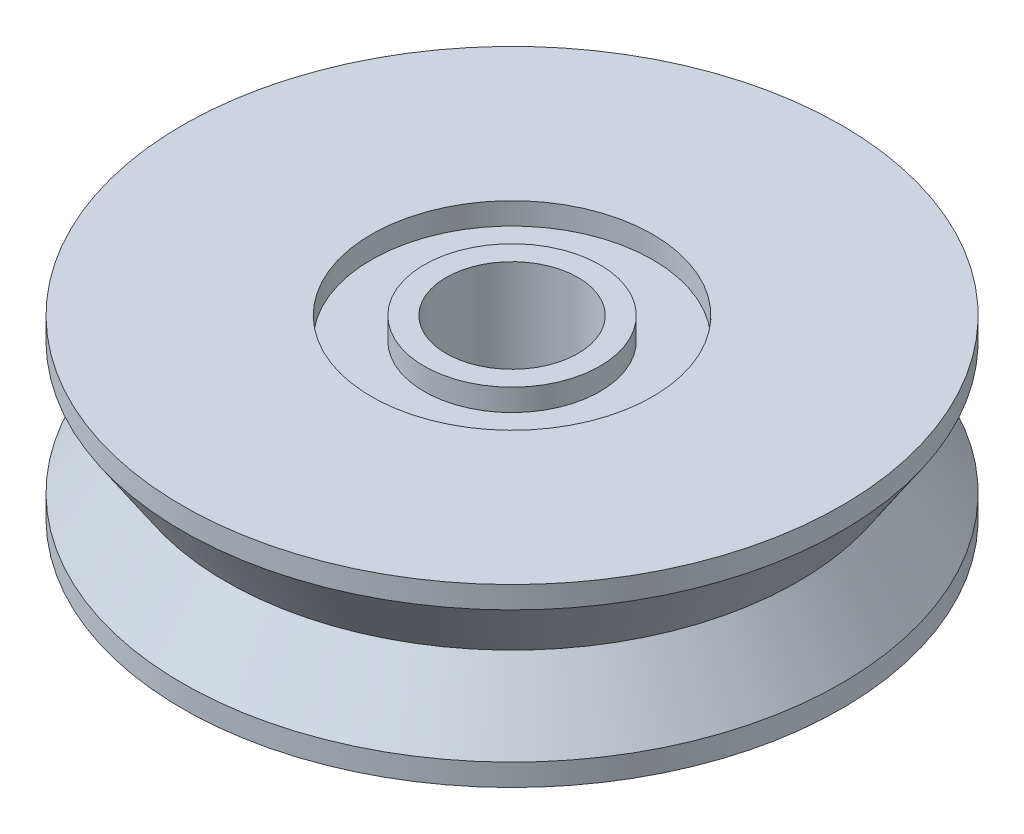
SolidWorks part; units mm, degrees
ref_plane "Front Plane" through (0, 0, 0) normal (0, 0, 1) x (1, 0, 0)
ref_plane "Top Plane" through (0, 0, 0) normal (0, 1, 0) x (1, 0, 0)
ref_plane "Right Plane" through (0, 0, 0) normal (1, 0, 0) x (0, 0, -1)
sketch "Sketch1" plane through (0, 0, 0) normal (0, 0, 1) x (1, 0, 0)
  line L0 (0, 0) -> (-1.5, 0) construction
  line L1 (-1.5, 0) -> (-1.5, 2)
  line L2 (-1.5, 2) -> (-2, 2)
  line L3 (-2, 2) -> (-2, 1.5)
  line L4 (-2, 1.5) -> (-3.2, 1.5)
  line L5 (-3.2, 1.5) -> (-3.2, 2)
  line L6 (-3.2, 2) -> (-7.5, 2)
  line L7 (-7.5, 2) -> (-7.5, 1.5)
  line L8 (-7.5, 1.5) -> (-6.5, 0)
  line L9 (-6.5, 0) -> (-1.5, 0)
  line L10 (0, 0) -> (0, 3.257) construction
  dimension "D1" = 1.5
  dimension "D2" = 0.5
  dimension "D3" = 1.2
  dimension "D4" = 0.5
  dimension "D5" = 2
  dimension "D6" = 6
  dimension "D7" = 5
revolve "Revolve1" add sketch "Sketch1" angle 360 about L10
mirror "Mirror1" about plane through (-6.5, 0, 0) normal (0, 1, 0) of "Revolve1"
